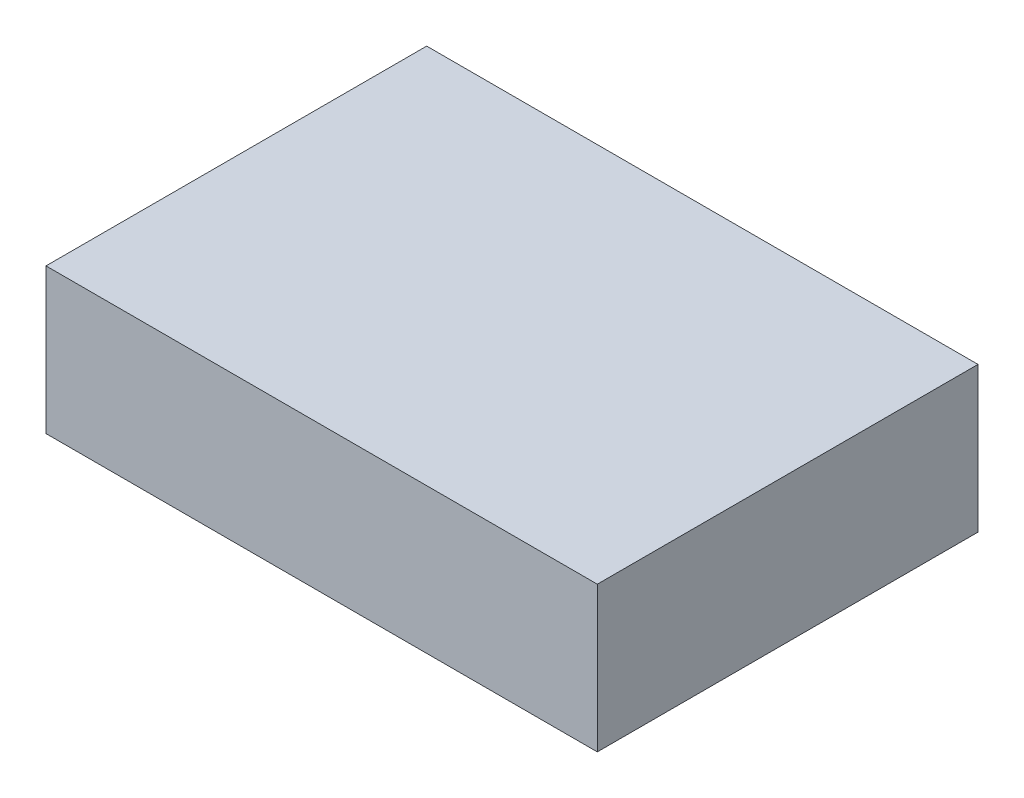
SolidWorks part; units mm, degrees
ref_plane "Front" through (0, 0, 0) normal (0, 0, 1) x (1, 0, 0)
ref_plane "Top" through (0, 0, 0) normal (0, 1, 0) x (1, 0, 0)
ref_plane "Right" through (0, 0, 0) normal (1, 0, 0) x (0, 0, -1)
sketch "Sketch1" plane through (0, 0, 0) normal (0, 1, 0) x (1, 0, 0)
  line L1 (-16.51, 11.4) -> (16.51, 11.4)
  line L2 (-16.51, 11.4) -> (-16.51, -11.4)
  line L3 (-16.51, -11.4) -> (16.51, -11.4)
  line L4 (16.51, 11.4) -> (16.51, -11.4)
  line L5 (-16.51, 11.4) -> (16.51, -11.4) construction
  line L6 (-16.51, -11.4) -> (16.51, 11.4) construction
  point P0 (0, 0)
  dimension "D1" = 33.02
  dimension "D2" = 22.8
extrude "Boss-Extrude1" add sketch "Sketch1" along normal blind 8.7
